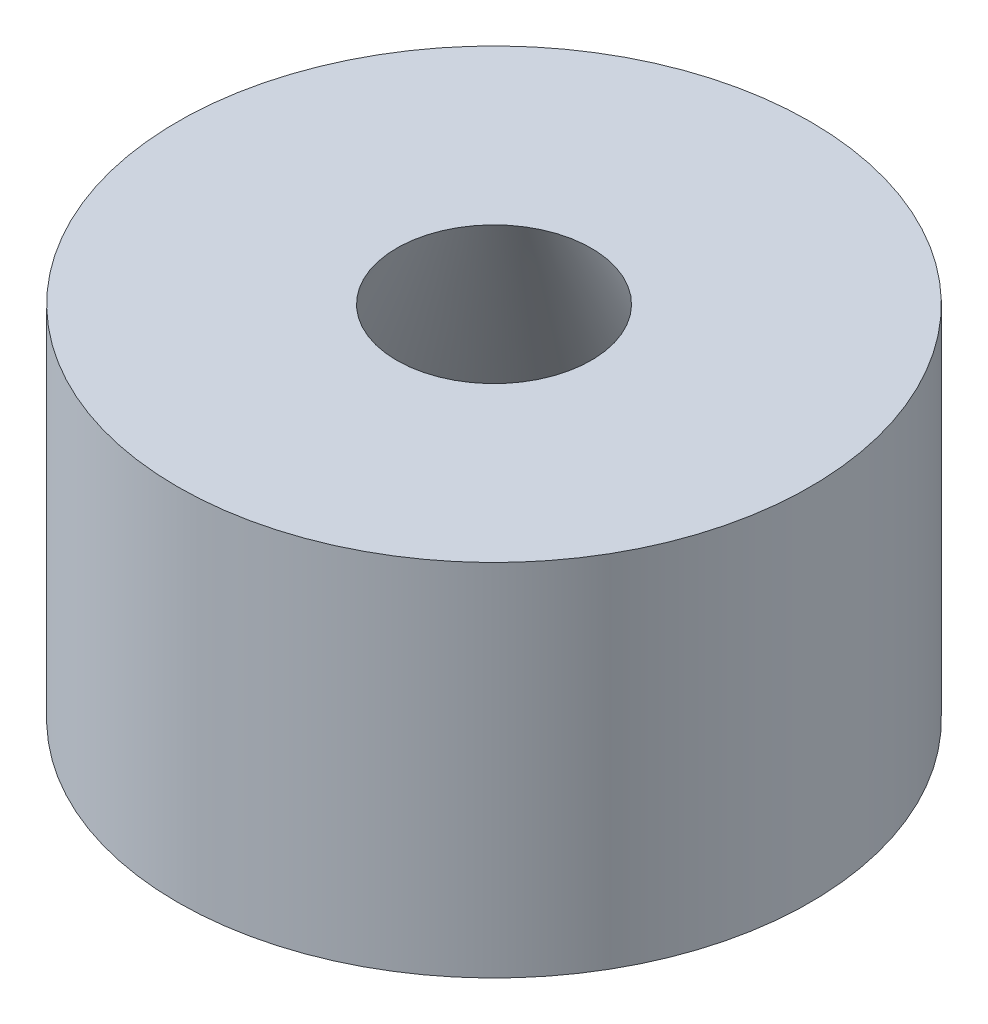
SolidWorks part; units mm, degrees
ref_plane "Front Plane" through (0, 0, 0) normal (0, 0, 1) x (1, 0, 0)
ref_plane "Top Plane" through (0, 0, 0) normal (0, 1, 0) x (1, 0, 0)
ref_plane "Right Plane" through (0, 0, 0) normal (1, 0, 0) x (0, 0, -1)
sketch "Sketch1" plane through (0, 0, 0) normal (0, 1, 0) x (1, 0, 0)
  circle A0 centre (0, 0) radius 8.79
  circle A1 centre (0, 0) radius 7.58
  dimension "D1" = 15.16
  dimension "D2" = 17.58
extrude "Boss-Extrude1" add sketch "Sketch1" along normal blind 10
draft "Draft3" type of draft neutral plane draft angle 26 faces to draft 1 face at (0, 10, 7.58) neutral plane through (0, 0, 0) neutral plane normal (0, -1, 0) parameters "D1"=26
sketch "Sketch2" plane through (0, 10, 0) normal (0, 1, 0) x (1, 0, 0)
  circle A0 centre (0, 0) radius 2.5
  dimension "D1" = 5
